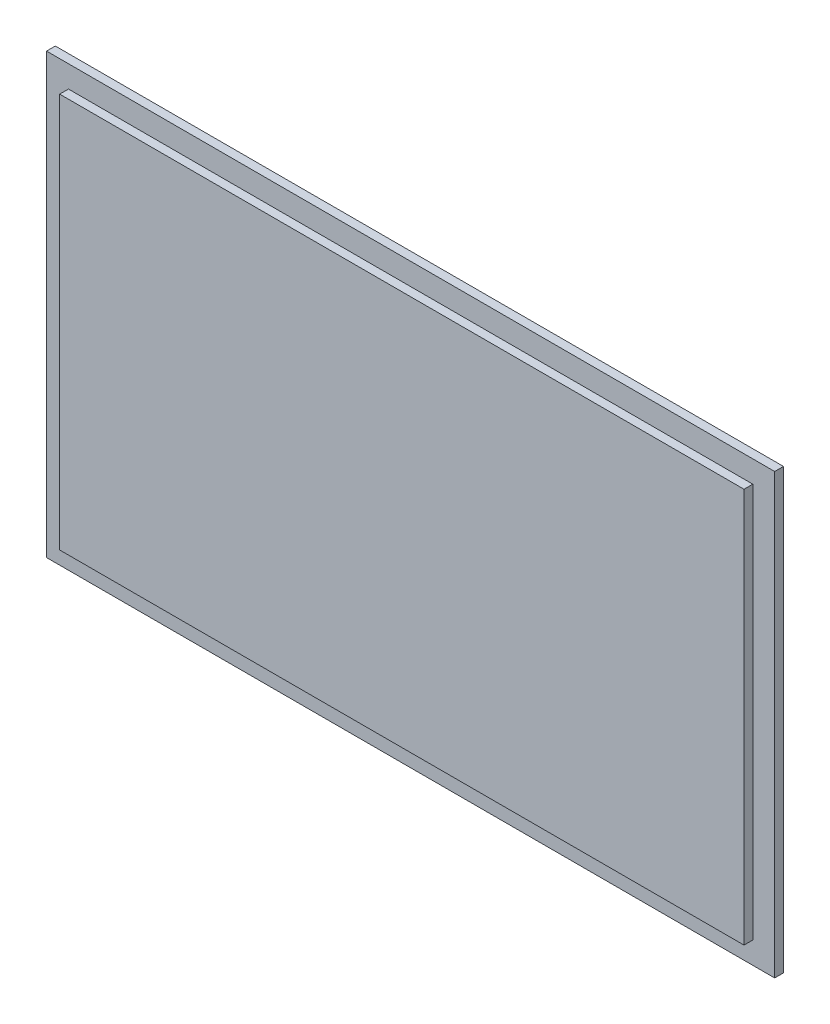
SolidWorks part; units mm, degrees
ref_plane "Front Plane" through (0, 0, 0) normal (0, 0, 1) x (1, 0, 0)
ref_plane "Top Plane" through (0, 0, 0) normal (0, 1, 0) x (1, 0, 0)
ref_plane "Right Plane" through (0, 0, 0) normal (1, 0, 0) x (0, 0, -1)
sketch "Sketch1" plane through (0, 0, 0) normal (0, 0, 1) x (1, 0, 0)
  line L1 (78, -45) -> (-78, -45)
  line L2 (78, -45) -> (78, 45)
  line L3 (78, 45) -> (-78, 45)
  line L4 (-78, -45) -> (-78, 45)
  line L5 (78, -45) -> (-78, 45) construction
  line L6 (78, 45) -> (-78, -45) construction
  point P0 (0, 0)
  dimension "D1" = 90
  dimension "D2" = 156
extrude "Boss-Extrude1" add sketch "Sketch1" along normal blind 2
sketch "Sketch2" plane through (0, 0, 0) normal (0, 0, -1) x (-1, 0, 0)
  line L0 (83, 50) -> (-83, 50)
  line L1 (-83, 50) -> (-83, -50)
  line L2 (-83, -50) -> (83, -50)
  line L3 (83, -50) -> (83, 50)
  line L4 (78, -45) -> (78, 45)
  line L5 (78, 45) -> (-78, 45)
  line L6 (-78, 45) -> (-78, -45)
  line L7 (-78, -45) -> (78, -45)
  line L8 (78, -45) -> (78, 45)
  line L9 (78, 45) -> (-78, 45)
  line L10 (-78, 45) -> (-78, -45)
  line L11 (-78, -45) -> (78, -45)
  dimension "D1" = 0
  dimension "D2" = 5
extrude "Boss-Extrude2" add sketch "Sketch2" along normal blind 2 separate body
